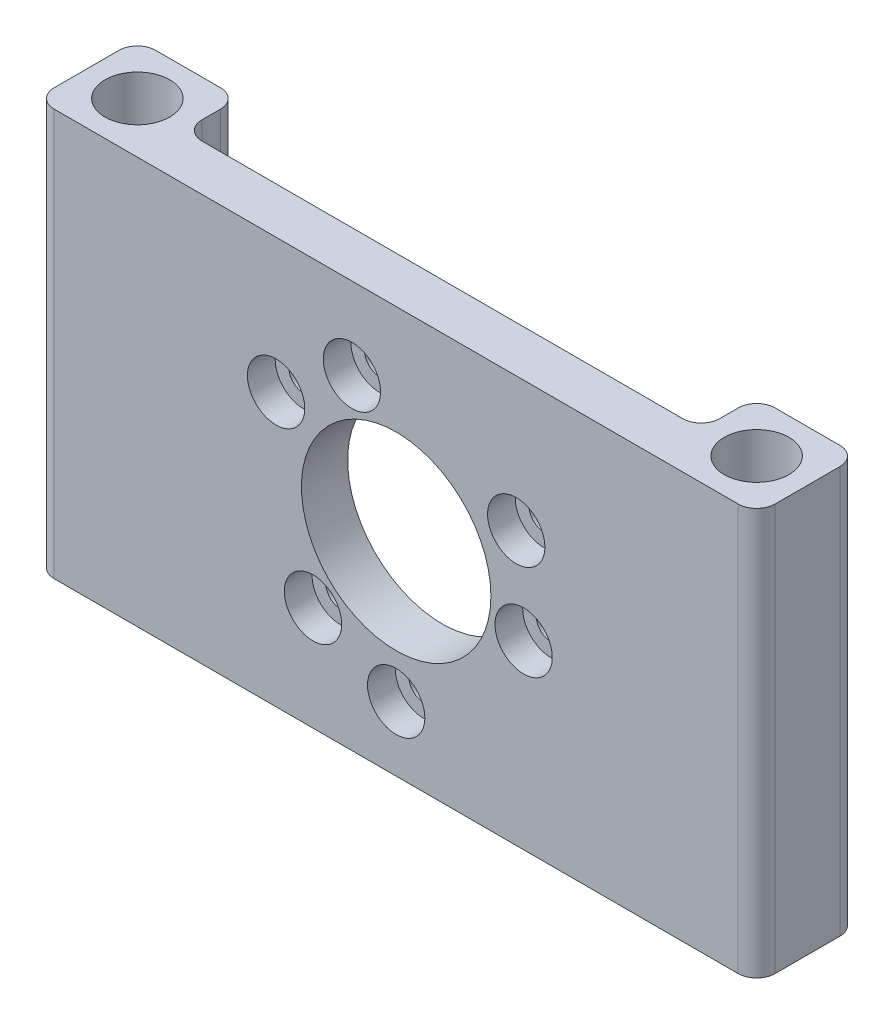
SolidWorks part; units mm, degrees
ref_plane "Plan de face" through (0, 0, 0) normal (0, 0, 1) x (1, 0, 0)
ref_plane "Plan de dessus" through (0, 0, 0) normal (0, 1, 0) x (1, 0, 0)
ref_plane "Plan de droite" through (0, 0, 0) normal (1, 0, 0) x (0, 0, -1)
sketch "Esquisse3" plane through (0, 0, 0) normal (0, 1, 0) x (1, 0, 0)
  line L0 (0, 32.7075) -> (0, -61.5486) construction
  line L1 (26, 0) -> (-26, 0)
  line L2 (-28, 2) -> (-28, 4)
  line L3 (-30, 6) -> (-37, 6)
  line L4 (-39, 4) -> (-39, -3)
  line L5 (-37, -5) -> (37, -5)
  line L7 (39, 4) -> (39, -3)
  line L8 (30, 6) -> (37, 6)
  line L9 (28, 2) -> (28, 4)
  circle A0 centre (-33.5, 0.5) radius 3.5
  circle A1 centre (33.5, 0.5) radius 3.5
  arc A2 (39, -3) -> (37, -5) centre (37, -3) cw
  arc A3 (39, 4) -> (37, 6) centre (37, 4) ccw
  arc A4 (30, 6) -> (28, 4) centre (30, 4) ccw
  arc A5 (28, 2) -> (26, 0) centre (26, 2) cw
  arc A6 (-26, 0) -> (-28, 2) centre (-26, 2) cw
  arc A7 (-28, 4) -> (-30, 6) centre (-30, 4) ccw
  arc A8 (-39, -3) -> (-37, -5) centre (-37, -3) ccw
  arc A9 (-37, 6) -> (-39, 4) centre (-37, 4) ccw
  point P17 (39, -5)
  point P20 (39, 6)
  point P23 (28, 6)
  point P26 (28, 0)
  point P29 (-28, 0)
  point P32 (-28, 6)
  point P35 (-39, -5)
  point P38 (-39, 6)
  dimension "D5" = 7
  dimension "D9" = 2
  dimension "D10" = 7
  dimension "D11" = 5.5
  dimension "D1" = 78
  dimension "D2" = 5
  dimension "D3" = 6
  dimension "D4" = 11
  dimension "D6" = 5.5
  dimension "D7" = 5.5
  dimension "D8" = 67
extrude "Boss.-Extru.1" add sketch "Esquisse3" along normal blind 44
sketch "Esquisse4" plane through (0, 0, 5) normal (0, 0, 1) x (1, 0, 0)
  line L0 (37, 22) -> (-37, 22) construction
  line L1 (37, 44) -> (37, 0) construction
  line L2 (0, 72.1736) -> (0, -28.1736) construction
  line L3 (0, 22) -> (-21.3762, -3.4752) construction
  line L4 (-37, 44) -> (-37, 0) construction
  line L5 (-37, 0) -> (37, 0) construction
  circle A0 centre (0, 22) radius 10.25
  circle A1 centre (0, 7) radius 1.625
  circle A2 centre (-8.999, 11.2754) radius 1.625
  circle A3 centre (13.7873, 19.5689) radius 1.625
  circle A4 centre (12.9904, 29.5) radius 1.625
  circle A5 centre (-4.7883, 35.1557) radius 1.625
  circle A6 centre (-12.9904, 29.5) radius 1.625
  point P29 (0, 22)
  dimension "D1" = 20.5
  dimension "D2" = 40
  dimension "D4" = 3.25
  dimension "D5" = 3.25
  dimension "D3" = 15
  dimension "D6" = 14
  dimension "D8" = 22
  dimension "D7" = 3
extrude "Enlèv. mat.-Extru.1" cut sketch "Esquisse4" against normal blind 60
sketch "Esquisse6" plane through (0, 0, 5) normal (0, 0, 1) x (1, 0, 0)
  circle A1 centre (-8.999, 11.2754) radius 1.625 construction
  circle A2 centre (0, 22) radius 10.25 construction
  circle A4 centre (0, 22) radius 10.25
  circle A6 centre (0, 7) radius 1.625 construction
  circle A7 centre (-8.999, 11.2754) radius 1.625
  circle A8 centre (0, 7) radius 1.625
  circle A9 centre (0, 7) radius 3.1
  circle A10 centre (-8.999, 11.2754) radius 3.1
  circle A11 centre (-4.7883, 35.1557) radius 3.1
  circle A12 centre (-12.9904, 29.5) radius 3.1
  circle A13 centre (13.7873, 19.5689) radius 3.1
  circle A14 centre (12.9904, 29.5) radius 3.1
  point P22 (0, 22)
  point P26 (-1.4036, 22.1228)
  circle M9 centre (12.9904, 29.5) radius 1.625
  dimension "D2" = 6.2
  dimension "D3" = 6.2
  dimension "D1" = 3
extrude "Enlèv. mat.-Extru.2" cut sketch "Esquisse6" against normal blind 3 and the other way through all contours A14 M9
